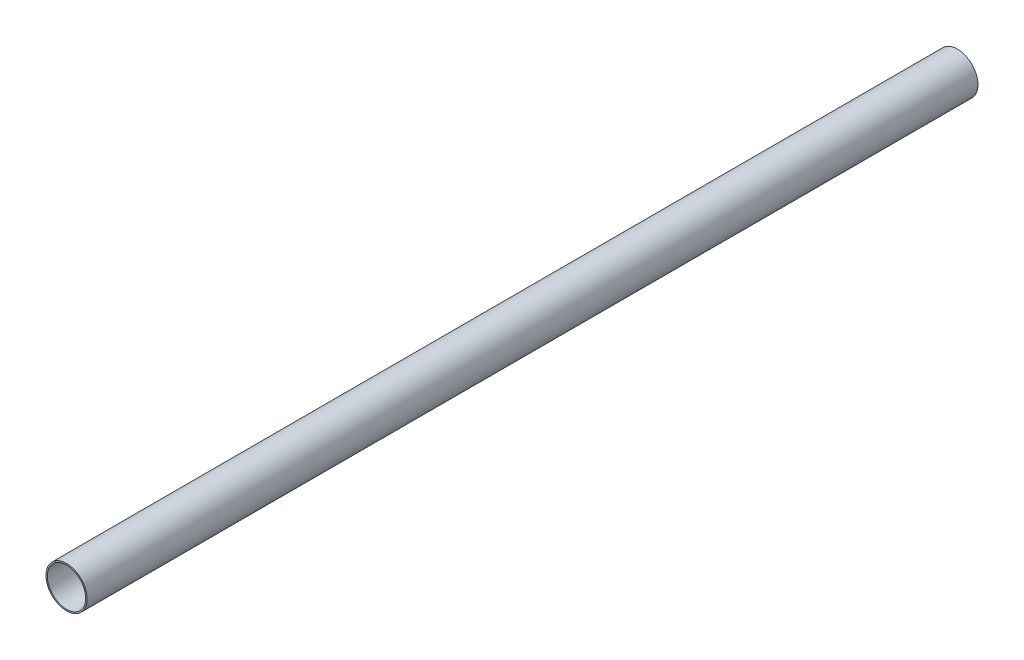
SolidWorks part; units mm, degrees
material "CarbonFiber"
ref_plane "Front Plane" through (0, 0, 0) normal (0, 0, 1) x (1, 0, 0)
ref_plane "Top Plane" through (0, 0, 0) normal (0, 1, 0) x (1, 0, 0)
ref_plane "Right Plane" through (0, 0, 0) normal (1, 0, 0) x (0, 0, -1)
sketch "Эскиз1" plane through (0, 0, 0) normal (0, 0, 1) x (1, 0, 0)
  circle A0 centre (0, 0) radius 15
  circle A1 centre (0, 0) radius 14
  dimension "D1" = 30
  dimension "D2" = 1
extrude "Бобышка-Вытянуть1" add sketch "Эскиз1" along normal mid plane 650
equation "\"DTailTube\"= 16мм'Диаметр трубки хвостового оперения"
equation "\"FusLenght\"= 700мм"
equation "\"DMotor\"= 35.2мм"
equation "\"MotorArm\"= 320мм"
equation "\"DFus\"= 150мм"
equation "\"DFusTube\"= 30мм'Диаметр трубки внутри фюзеляжа"
equation "\"FusTubeHeight\"= 40мм"
equation "\"FusCentralPartLenght\"= 410мм"
equation "\"FusNoseLenght\"= 150мм"
equation "\"WingOffset\"= 1мм'Расстояние от внутренней поверхности фюзеляжа до профиля крыла по вертикали"
equation "\"EllipseRatio\"= 0.95'Центральная часть фюзеляжа - эллипс. Этот параметр - отношение длин осей эллипса"
equation "\"FrameOffset\"= 0.6мм"
equation "\"DThreadedInsert\"= 3.6мм'Внешний диамер резьбовых втулок"
equation "\"CenterSectionLenght\"= 140мм'Длина центроплана"
equation "\"b\"= 1700мм'Размах"
equation "\"cwr\"= 236мм'Корневая хорда крыла"
equation "\"TR\"= 0.75'Сужение крыла"
equation "\"cwt\"= \"TR\" * \"cwr\"'Концевая хорда крыла"
equation "\"DWingMainSpar\"= 16мм'Диаметр главного лонжерона крыла"
equation "\"DWingSecondSpar\"= 8мм'Диаметр второго лонжерона крыла"
equation "\"WingSparsDistance\"= 80мм'Расстояния между отверстиями по лонжерон крыла"
equation "\"c\"= 210мм'САХ крыла"
equation "\"D1@Эскиз1\"=\"DFusTube\""
equation "\"D1@Бобышка-Вытянуть1\"=\"FusTubeLenght\""
equation "\"FusTubeLenght\"= \"FusLenght\"-50мм'Длина трубки фюзеляжа"
equation "\"bt\"=291мм'Высота лопатки хвоста"
equation "\"ct\"=182мм'Корневая хорда хвоста"
equation "\"lambda_t\"=0.3'Доля хвоста, занатая рулем высоты"
equation "\"TailTubeLenght\"=730мм'Длина хвостовой балки"
equation "\"DStringer\"=6мм'Диаметр стрингеров"
equation "\"TailConnectorBaseLenght\"=20мм'Высота основания конектора хвоста"
equation "\"CargoHolderHoleDistance\"=30мм'Расстояние между крепежными отверстиями для держателя груза"
equation "\"FuselageThickness\"=1.2мм'Толщина фюзеляжа"
equation "\"DTailSpar\"=6мм'Диаметр лонжерона хвостового оперения"
equation "\"TailSparDistance\"=40мм'Расстояние между лонжеронами хвостового оперения"
